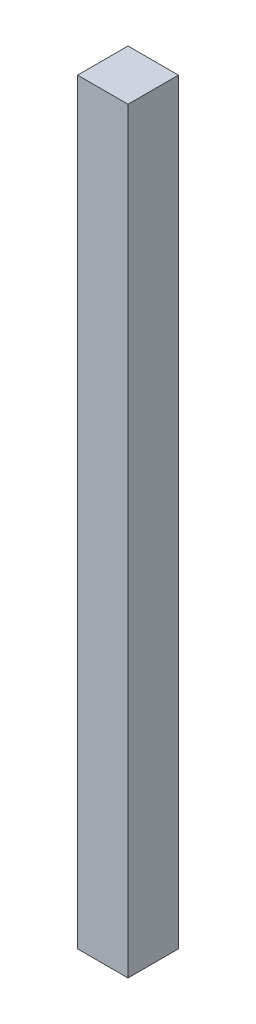
SolidWorks part; units mm, degrees
ref_plane "Front Plane" through (0, 0, 0) normal (0, 0, 1) x (1, 0, 0)
ref_plane "Top Plane" through (0, 0, 0) normal (0, 1, 0) x (1, 0, 0)
ref_plane "Right Plane" through (0, 0, 0) normal (1, 0, 0) x (0, 0, -1)
sketch "Sketch1" plane through (0, 0, 0) normal (0, 1, 0) x (1, 0, 0)
  line L1 (-25.4, -25.4) -> (25.4, -25.4)
  line L2 (-25.4, -25.4) -> (-25.4, 25.4)
  line L3 (-25.4, 25.4) -> (25.4, 25.4)
  line L4 (25.4, -25.4) -> (25.4, 25.4)
  line L5 (-25.4, -25.4) -> (25.4, 25.4) construction
  line L6 (-25.4, 25.4) -> (25.4, -25.4) construction
  point P0 (0, 0)
  dimension "D1" = 50.8
  dimension "D2" = 50.8
extrude "Boss-Extrude1" add sketch "Sketch1" along normal blind 762
sketch "Sketch2" plane through (0, 0, 0) normal (0, 1, 0) x (1, 0, 0)
  line L1 (-19.05, -19.05) -> (19.05, -19.05)
  line L2 (-19.05, -19.05) -> (-19.05, 19.05)
  line L3 (-19.05, 19.05) -> (19.05, 19.05)
  line L4 (19.05, -19.05) -> (19.05, 19.05)
  line L5 (-19.05, -19.05) -> (19.05, 19.05) construction
  line L6 (-19.05, 19.05) -> (19.05, -19.05) construction
  point P0 (0, 0)
  dimension "D1" = 38.1
  dimension "D2" = 38.1
